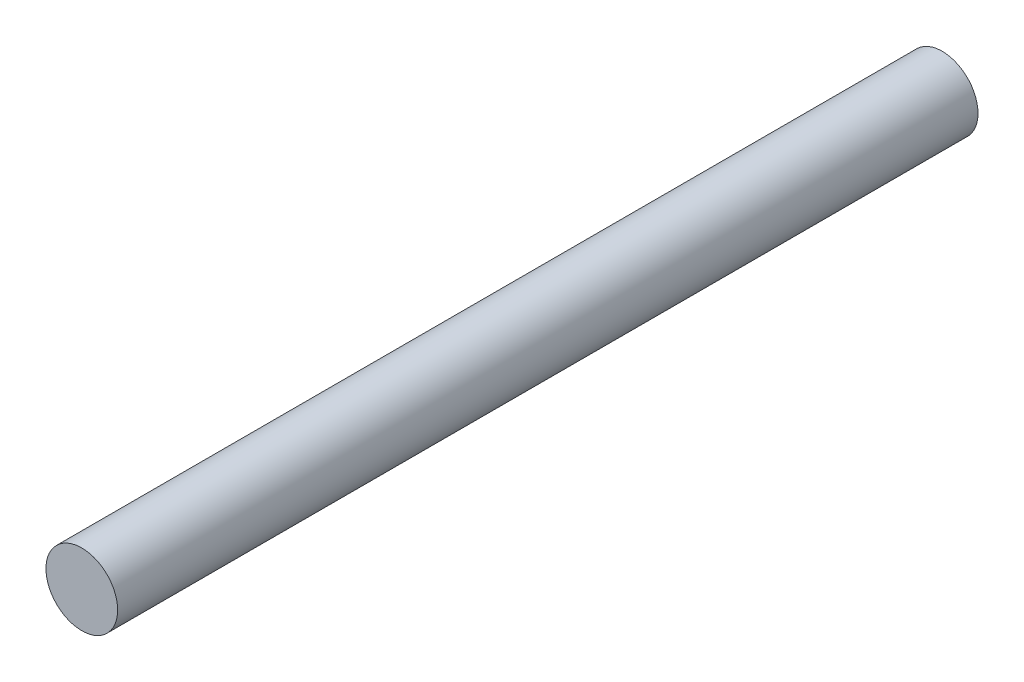
SolidWorks part; units mm, degrees
ref_plane "前视基准面" through (0, 0, 0) normal (0, 0, 1) x (1, 0, 0)
ref_plane "上视基准面" through (0, 0, 0) normal (0, 1, 0) x (1, 0, 0)
ref_plane "右视基准面" through (0, 0, 0) normal (1, 0, 0) x (0, 0, -1)
other "Configuration Table"
sketch "草图1" plane through (0, 0, 0) normal (0, 0, 1) x (1, 0, 0)
  circle A0 centre (0, 0) radius 2.5
  dimension "D1" = 5
extrude "凸台-拉伸1" add sketch "草图1" along normal blind 60
